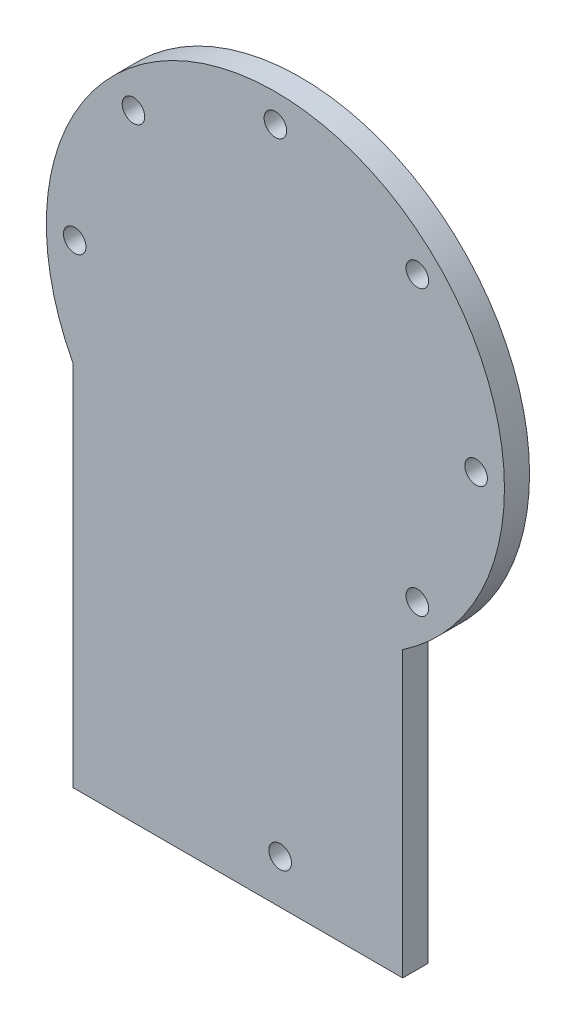
SolidWorks part; units mm, degrees
ref_plane "Plan de face" through (0, 0, 0) normal (0, 0, 1) x (1, 0, 0)
ref_plane "Plan de dessus" through (0, 0, 0) normal (0, 1, 0) x (1, 0, 0)
ref_plane "Plan de droite" through (0, 0, 0) normal (1, 0, 0) x (0, 0, -1)
sketch "Esquisse1" plane through (0, 0, 0) normal (0, 0, 1) x (1, 0, 0)
  line L0 (-22.3, -14.6685) -> (-22.3, -44)
  line L1 (-22.3, -44) -> (4, -44)
  line L2 (4, -44) -> (4, -21.3278)
  arc A0 (4, -21.3278) -> (-22.3, -14.6685) centre (-6.15, -6.15) ccw
extrude "Boss.-Extru.1" add sketch "Esquisse1" along normal blind 2
sketch "Esquisse2" plane through (0, 0, 2) normal (0, 0, 1) x (1, 0, 0)
  circle A0 centre (-6.15, -6.15) radius 16 construction
  circle A1 centre (9.85, -6.15) radius 0.9
  circle A2 centre (5.1637, -17.4637) radius 0.9
  circle A5 centre (-22.15, -6.15) radius 0.9
  circle A6 centre (-17.4637, 5.1637) radius 0.9
  circle A7 centre (-6.15, 9.85) radius 0.9
  circle A8 centre (5.1637, 5.1637) radius 0.9
  circle A9 centre (-17.4637, -17.4637) radius 0.9 [skipped]
  circle A10 centre (-6.15, -22.15) radius 0.9 [skipped]
  point P22 (-6.15, -6.15)
  dimension "D1" = 8
extrude "Enlèv. mat.-Extru.1" cut sketch "Esquisse2" against normal through all
sketch "Esquisse3" plane through (0, 0, 0) normal (0, 0, -1) x (-1, 0, 0)
  circle A0 centre (5.77, -40.5) radius 0.9
extrude "Enlèv. mat.-Extru.2" cut sketch "Esquisse3" against normal through all
